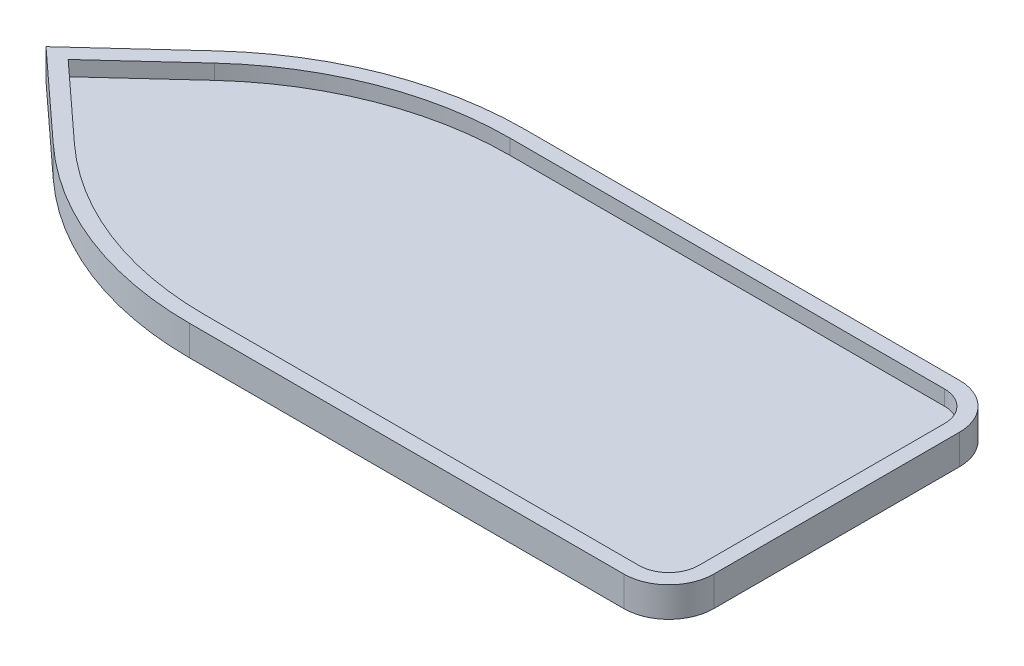
SolidWorks part; units mm, degrees
ref_plane "Front Plane" through (0, 0, 0) normal (0, 0, 1) x (1, 0, 0)
ref_plane "Top Plane" through (0, 0, 0) normal (0, 1, 0) x (1, 0, 0)
ref_plane "Right Plane" through (0, 0, 0) normal (1, 0, 0) x (0, 0, -1)
sketch "Sketch1" plane through (0, 0, 0) normal (0, 1, 0) x (1, 0, 0)
  line L0 (0, -15) -> (0, -97)
  line L1 (-15, 0) -> (-160, 0)
  line L3 (-160, -112) -> (-15, -112)
  line L5 (-234.375, -28.9546) -> (-263.846, -56)
  line L6 (-263.846, -56) -> (-234.375, -83.0454)
  arc A0 (-234.375, -28.9546) -> (-160, 0) centre (-160, -110) cw
  arc A1 (-160, -112) -> (-234.375, -83.0454) centre (-160, -2) cw
  arc A2 (0, -15) -> (-15, 0) centre (-15, -15) ccw
  arc A3 (0, -97) -> (-15, -112) centre (-15, -97) cw
  point P5 (0, 0)
  point P13 (0, 0)
  point P16 (0, -112)
  dimension "D3" = 110
  dimension "D4" = 160
  dimension "D1" = 110
  dimension "D8" = 15
  dimension "D9" = 15
  dimension "D2" = 112
  dimension "D5" = 160
  dimension "D6" = 40
  dimension "D7" = 40
extrude "Boss-Extrude1" add sketch "Sketch1" along normal blind 10
shell "Shell1" thickness 5
